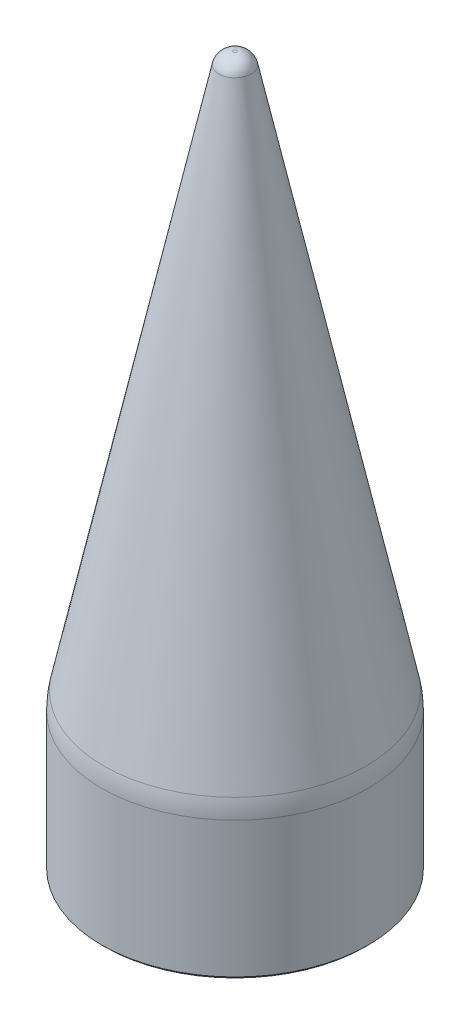
SolidWorks part; units mm, degrees
ref_plane "前视基准面" through (0, 0, 0) normal (0, 0, 1) x (1, 0, 0)
ref_plane "上视基准面" through (0, 0, 0) normal (0, 1, 0) x (1, 0, 0)
ref_plane "右视基准面" through (0, 0, 0) normal (1, 0, 0) x (0, 0, -1)
other "Configuration Table"
sketch "草图1" plane through (0, 0, 0) normal (0, 1, 0) x (1, 0, 0)
  circle A0 centre (0, 0) radius 45
  dimension "D1" = 90
extrude "凸台-拉伸1" add sketch "草图1" along normal blind 50
sketch "草图2" plane through (0, 0, 0) normal (0, -1, 0) x (-1, 0, 0)
  circle A0 centre (0, 0) radius 37.5
  dimension "D1" = 75
extrude "切除-拉伸1" cut sketch "草图2" against normal blind 50
ref_plane "基准面1" through (0, 0, 40) normal (0, 0, 1) x (1, 0, 0)
sketch "草图3" plane through (0, 0, 40) normal (0, 0, 1) x (1, 0, 0)
  line L0 (45, 50) -> (-45, 50) construction
  circle A0 centre (0, 25) radius 7.5
  dimension "D1" = 15
  dimension "D2" = 25
extrude "凸台-拉伸2" add sketch "草图3" against normal blind 80
sketch "草图4" plane through (0, 50, 0) normal (0, 1, 0) x (1, 0, 0)
  circle A0 centre (0, 0) radius 45
  dimension "D1" = 90
extrude "凸台-拉伸3" add sketch "草图4" along normal blind 190 draft 12
fillet "圆角1" radius 5 1 edges at (0, 240, 4.6143)
fillet "圆角2" radius 30 1 edges at (0, 50, 45)
chamfer "倒角1" distance 1 angle 45 2 edges at (0, 0, 45) (0, 0, -37.5)
